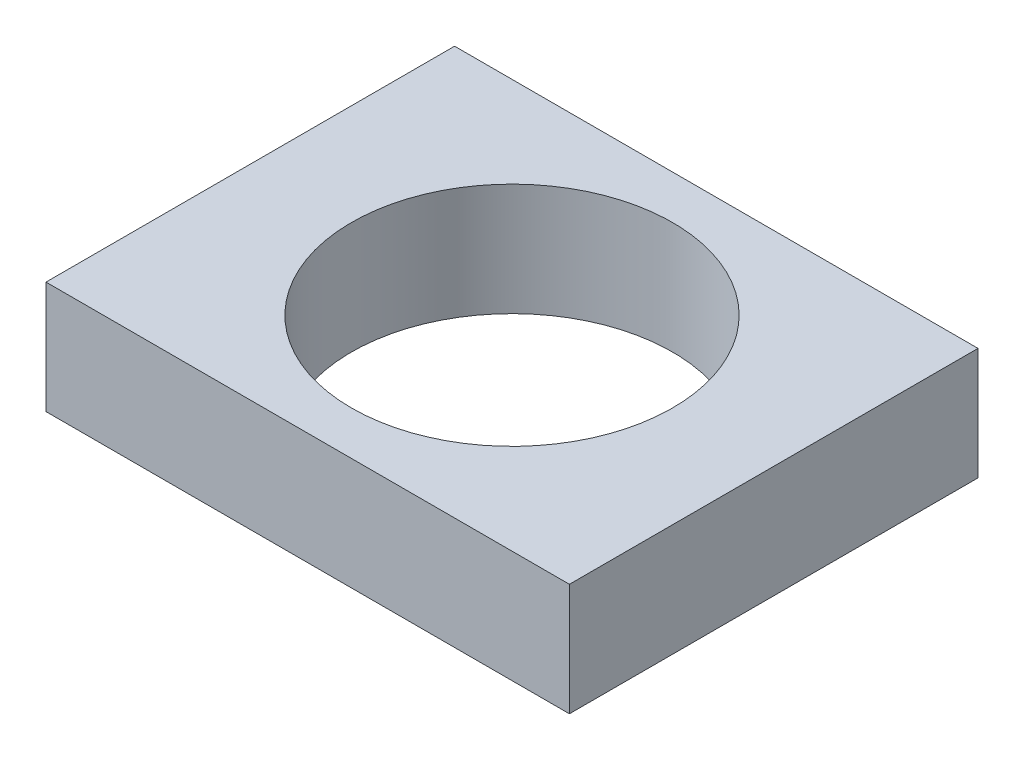
SolidWorks part; units mm, degrees
ref_plane "Front Plane" through (0, 0, 0) normal (0, 0, 1) x (1, 0, 0)
ref_plane "Top Plane" through (0, 0, 0) normal (0, 1, 0) x (1, 0, 0)
ref_plane "Right Plane" through (0, 0, 0) normal (1, 0, 0) x (0, 0, -1)
sketch "Sketch3" plane through (0, 0, 0) normal (0, 1, 0) x (1, 0, 0)
  line L1 (0, 0) -> (59.2551, 0)
  line L2 (0, 0) -> (0, 46.2565)
  line L3 (0, 46.2565) -> (59.2551, 46.2565)
  line L4 (59.2551, 0) -> (59.2551, 46.2565)
  circle A0 centre (29.6276, 23.1282) radius 18.1822
extrude "Extrude3" add sketch "Sketch3" against normal blind 12.7
